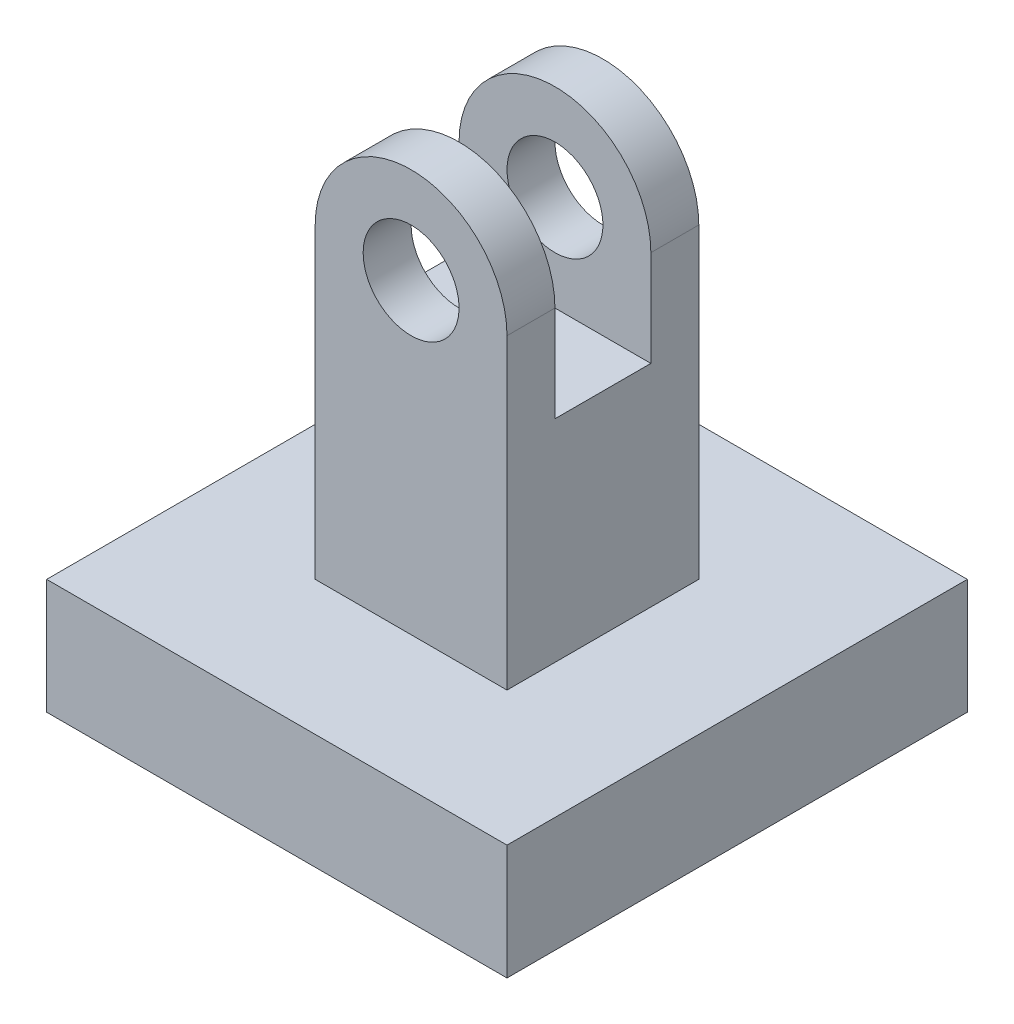
SolidWorks part; units mm, degrees
ref_plane "前视基准面" through (0, 0, 0) normal (0, 0, 1) x (1, 0, 0)
ref_plane "上视基准面" through (0, 0, 0) normal (0, 1, 0) x (1, 0, 0)
ref_plane "右视基准面" through (0, 0, 0) normal (1, 0, 0) x (0, 0, -1)
other "Configuration Table"
sketch "草图1" plane through (0, 0, 0) normal (0, 1, 0) x (1, 0, 0)
  line L1 (-30, 30) -> (30, 30)
  line L2 (-30, 30) -> (-30, -30)
  line L3 (-30, -30) -> (30, -30)
  line L4 (30, 30) -> (30, -30)
  line L5 (-30, 30) -> (30, -30) construction
  line L6 (-30, -30) -> (30, 30) construction
  point P0 (0, 0)
  dimension "D1" = 60
  dimension "D2" = 60
extrude "凸台-拉伸1" add sketch "草图1" along normal blind 15
sketch "草图2" plane through (0, 0, 0) normal (0, 1, 0) x (1, 0, 0)
  line L1 (-12.5, 12.5) -> (12.5, 12.5)
  line L2 (-12.5, 12.5) -> (-12.5, -12.5)
  line L3 (-12.5, -12.5) -> (12.5, -12.5)
  line L4 (12.5, 12.5) -> (12.5, -12.5)
  line L5 (-12.5, 12.5) -> (12.5, -12.5) construction
  line L6 (-12.5, -12.5) -> (12.5, 12.5) construction
  point P0 (0, 0)
  dimension "D1" = 25
  dimension "D2" = 25
extrude "凸台-拉伸2" add sketch "草图2" along normal blind 40 from surface at 15 starting at face at (0, 15, 0)
sketch "草图6" plane through (0, 0, 0) normal (0, 0, 1) x (1, 0, 0)
  line L0 (12.5, 55) -> (-12.5, 55) construction
  line L1 (-12.5, 55) -> (12.5, 55)
  arc A0 (12.5, 55) -> (-12.5, 55) centre (0, 55) ccw
extrude "凸台-拉伸3" add sketch "草图6" against normal up to surface (25 mm away) from surface at 12.5 up to face at (0, 35, -12.5) starting at face at (0, 35, 12.5)
sketch "草图8" plane through (0, 0, 0) normal (0, 0, 1) x (1, 0, 0)
  arc A0 (12.5, 55) -> (-12.5, 55) centre (0, 55) ccw construction
  arc A1 (12.5, 55) -> (-12.5, 55) centre (0, 55) ccw construction
  circle A2 centre (0, 55) radius 6.25
  dimension "D1" = 12.5
extrude "切除-拉伸5" cut sketch "草图8" along normal up to surface (25 mm away) from surface at -12.5 up to face at (0, 38.125, 12.5) starting at face at (0, 38.125, -12.5)
sketch "草图9" plane through (0, 0, 0) normal (0, 0, 1) x (1, 0, 0)
  line L1 (-12.5, 42.5) -> (12.5, 42.5)
  line L2 (-12.5, 42.5) -> (-12.5, 67.5)
  line L3 (-12.5, 67.5) -> (12.5, 67.5)
  line L4 (12.5, 42.5) -> (12.5, 67.5)
  line L5 (-12.5, 42.5) -> (12.5, 67.5) construction
  line L6 (-12.5, 67.5) -> (12.5, 42.5) construction
  point P0 (0, 55)
  dimension "D1" = 25
  dimension "D2" = 25
extrude "切除-拉伸6" cut sketch "草图9" against normal blind 6.25 and the other way blind 6.25
